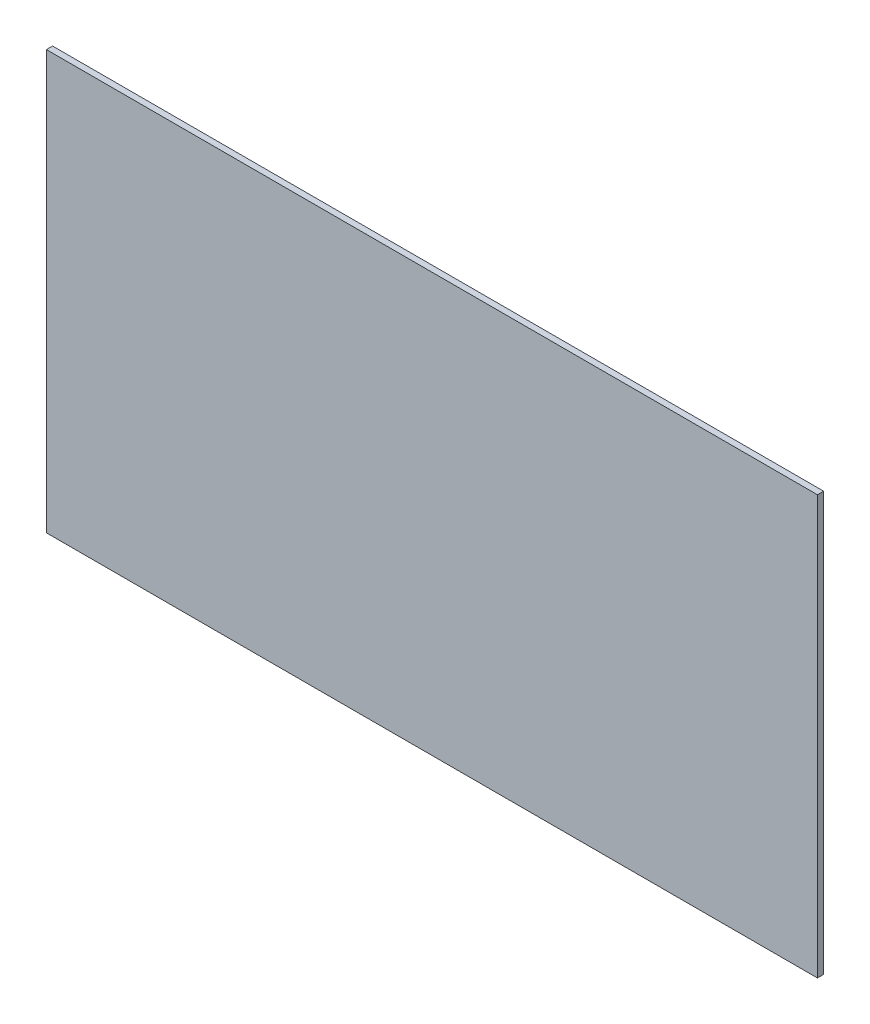
SolidWorks part; units mm, degrees
ref_plane "Plan de face" through (0, 0, 0) normal (0, 0, 1) x (1, 0, 0)
ref_plane "Plan de dessus" through (0, 0, 0) normal (0, 1, 0) x (1, 0, 0)
ref_plane "Plan de droite" through (0, 0, 0) normal (1, 0, 0) x (0, 0, -1)
sketch "Esquisse1" plane through (0, 0, 0) normal (0, 0, 1) x (1, 0, 0)
  line L1 (0, 0) -> (374, 0)
  line L2 (0, 0) -> (0, 203)
  line L3 (0, 203) -> (374, 203)
  line L4 (374, 0) -> (374, 203)
  dimension "D1" = 374
  dimension "D2" = 203
extrude "Boss.-Extru.1" add sketch "Esquisse1" along normal blind 3
